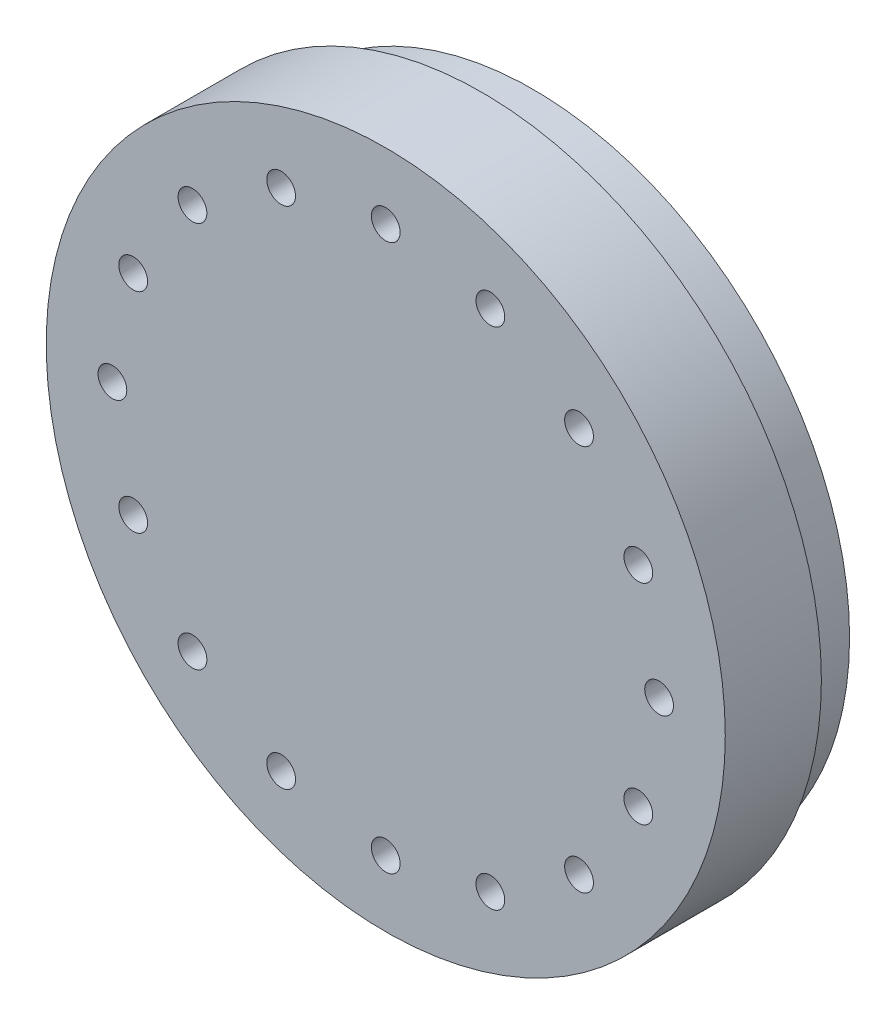
SolidWorks part; units mm, degrees
material "6061-T6 (SS)"
ref_plane "Front Plane" through (0, 0, 0) normal (0, 0, 1) x (1, 0, 0)
ref_plane "Top Plane" through (0, 0, 0) normal (0, 1, 0) x (1, 0, 0)
ref_plane "Right Plane" through (0, 0, 0) normal (1, 0, 0) x (0, 0, -1)
sketch "Sketch1" plane through (0, 0, 0) normal (0, 0, 1) x (1, 0, 0)
  circle A0 centre (0, 0) radius 29.5
  dimension "D1" = 59
extrude "Boss-Extrude1" add sketch "Sketch1" along normal mid plane 8.35
sketch "Sketch2" plane through (0, 0, -4.175) normal (0, 0, -1) x (-1, 0, 0)
  circle A0 centre (0, 0) radius 27.5
  dimension "D1" = 55
extrude "Boss-Extrude2" add sketch "Sketch2" along normal blind 4.45
sketch "Sketch3" plane through (0, 0, 4.175) normal (0, 0, 1) x (1, 0, 0)
  circle A0 centre (0, 0) radius 23.75 construction
  circle A1 centre (0, 23.75) radius 1.25
  dimension "D1" = 47.5
  dimension "D2" = 2.5
extrude "Cut-Extrude1" cut sketch "Sketch3" against normal through all
pattern_circular "CirPattern1" count 16 over 360 about axis through (0, 0, 0) along (0, 0, 1) of "Cut-Extrude1"
